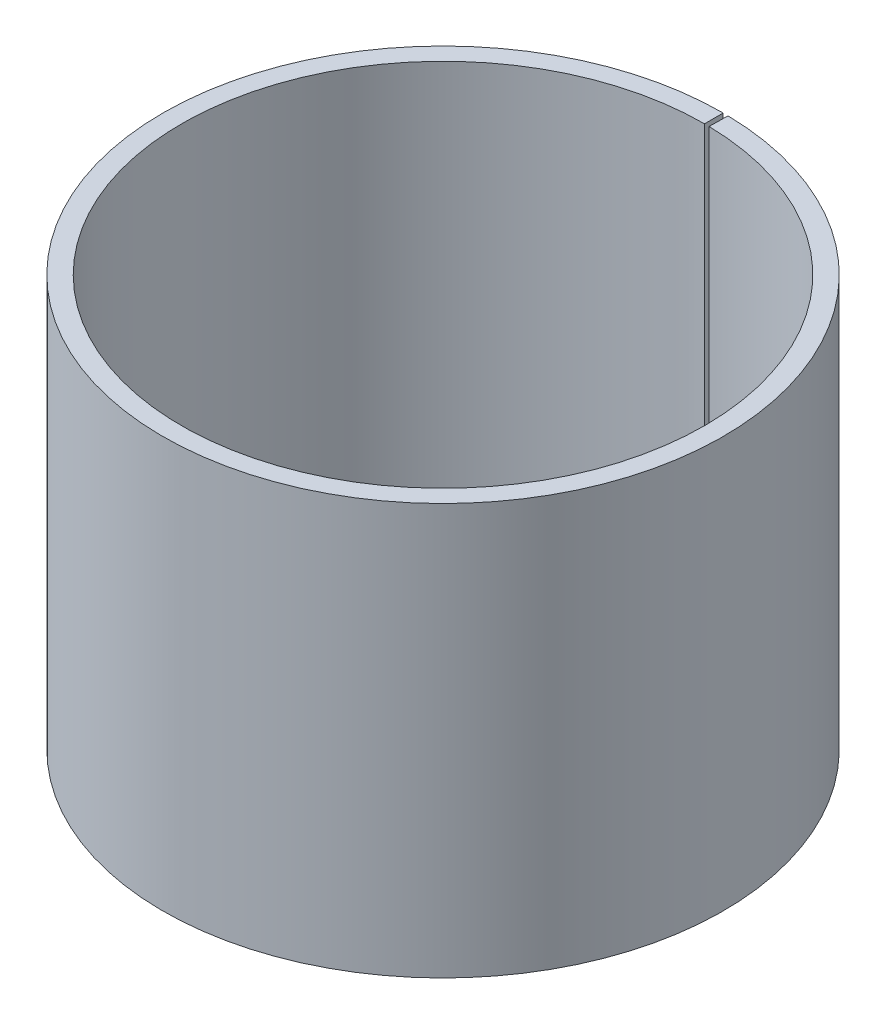
SolidWorks part; units mm, degrees
ref_plane "Front Plane" through (0, 0, 0) normal (0, 0, 1) x (1, 0, 0)
ref_plane "Top Plane" through (0, 0, 0) normal (0, 1, 0) x (1, 0, 0)
ref_plane "Right Plane" through (0, 0, 0) normal (1, 0, 0) x (0, 0, -1)
sketch "Sketch3" plane through (0, 0, 0) normal (1, 0, 0) x (0, 0, -1)
  line L0 (0, 0) -> (0, 70.3616) construction
  line L1 (106.68, 0) -> (106.68, 167.64)
  dimension "D1" = 167.64
  dimension "D2" = 106.68
revolve "Revolve-Thin3" add sketch "Sketch3" angle 359 about L0
equation "\"MDF\"= .3"
equation "\"Foamcore\"= .1"
equation "\"GMaterial\"= .3"
equation "\"CutDistance\" = .1"
equation "\"D3@Revolve-Thin3\"=\"GMaterial\""
equation "\"D1@Sketch3\"=2*\"GMaterial\" + 6"
equation "\"D2@Sketch3\"=4.5-\"GMaterial\""
equation "\"D1@Sketch11\"=\"GMaterial\""
